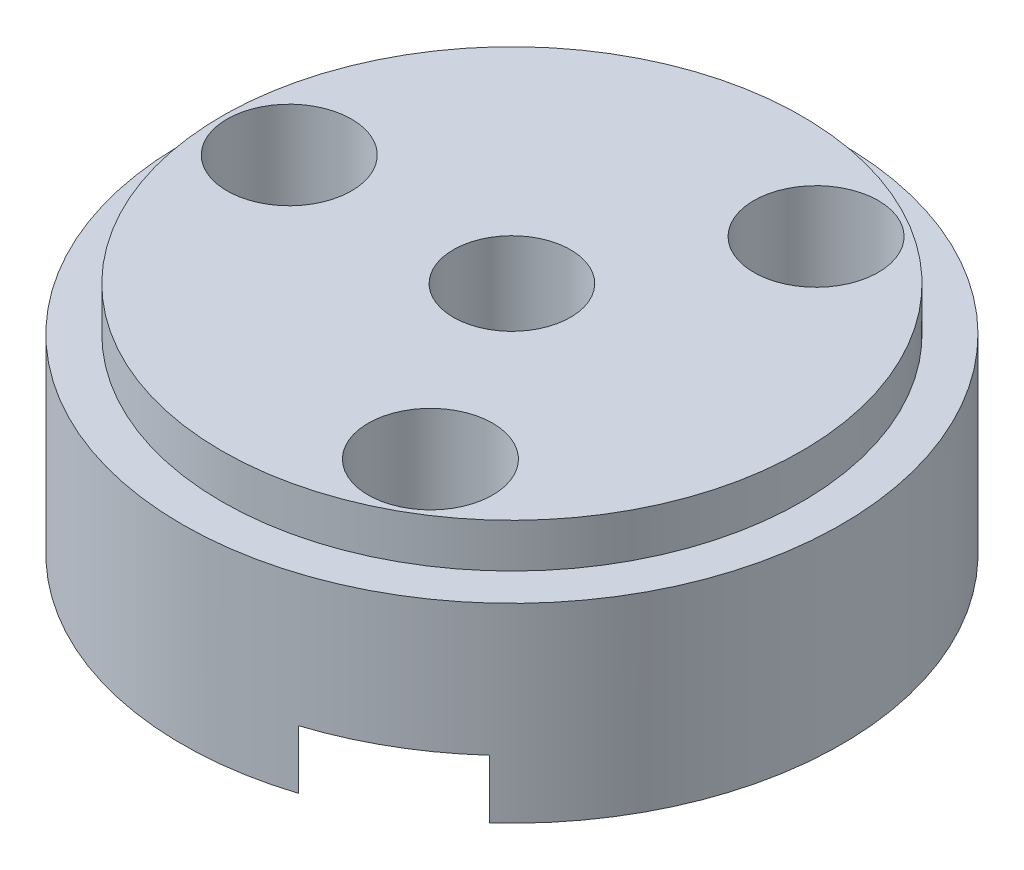
SolidWorks part; units mm, degrees
ref_plane "Front Plane" through (0, 0, 0) normal (0, 0, 1) x (1, 0, 0)
ref_plane "Top Plane" through (0, 0, 0) normal (0, 1, 0) x (1, 0, 0)
ref_plane "Right Plane" through (0, 0, 0) normal (1, 0, 0) x (0, 0, -1)
sketch "Sketch1" plane through (0, 0, 0) normal (0, 1, 0) x (1, 0, 0)
  circle A0 centre (0, 0) radius 11.25
  circle A1 centre (0, 0) radius 2
  dimension "D1" = 22.5
  dimension "D2" = 4
extrude "Boss-Extrude1" add sketch "Sketch1" along normal blind 8
sketch "Sketch2" plane through (0, 0, 0) normal (0, -1, 0) x (1, 0, 0)
  circle A0 centre (-7.6, 0) radius 2.125
  circle A1 centre (3.8, 6.5818) radius 2.125
  circle A2 centre (3.8, -6.5818) radius 2.125
  point P9 (0, 0)
  dimension "D2" = 4.25
  dimension "D1" = 7.6
  dimension "D3" = 3
extrude "Cut-Extrude1" cut sketch "Sketch2" against normal through all
sketch "Sketch3" plane through (0, 0, 0) normal (0, -1, 0) x (1, 0, 0)
  circle A0 centre (-7.6, 0) radius 4.15
  circle A1 centre (3.8, 6.5818) radius 4.15
  circle A2 centre (3.8, -6.5818) radius 4.15
  point P12 (0, 0)
  dimension "D1" = 8.3
  dimension "D2" = 3
extrude "Cut-Extrude2" cut sketch "Sketch3" against normal blind 2
sketch "Sketch4" plane through (0, 8, 0) normal (0, 1, 0) x (1, 0, 0)
  circle A0 centre (0, 0) radius 11.25
  circle A1 centre (0, 0) radius 9.9
  dimension "D1" = 19.8
extrude "Cut-Extrude3" cut sketch "Sketch4" against normal blind 1.5
